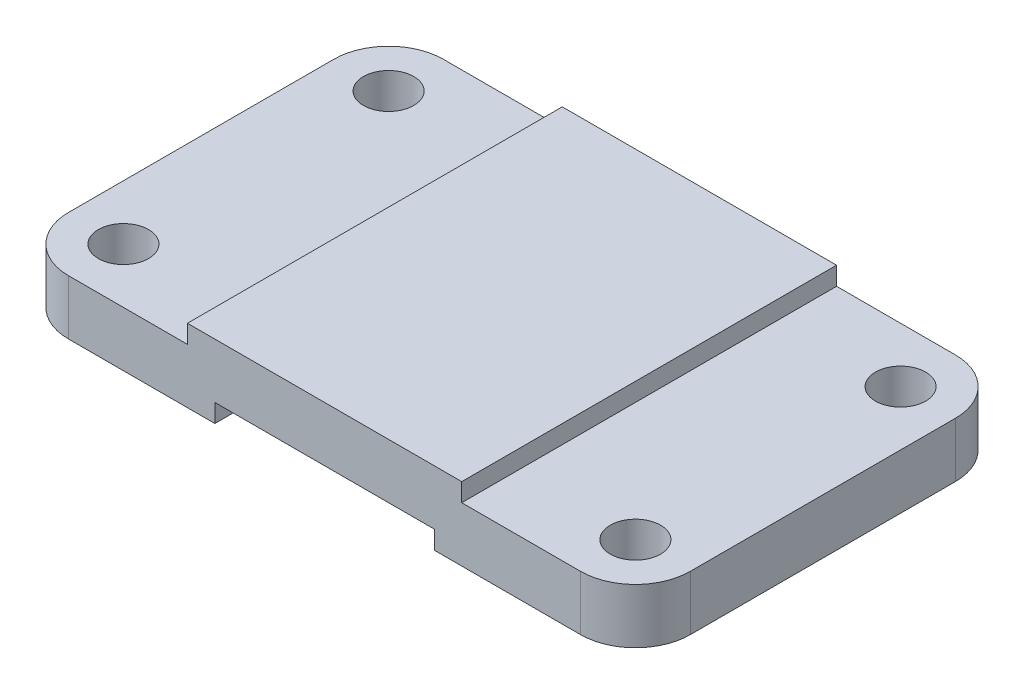
SolidWorks part; units mm, degrees
ref_plane "Plan de face" through (0, 0, 0) normal (0, 0, 1) x (1, 0, 0)
ref_plane "Plan de dessus" through (0, 0, 0) normal (0, 1, 0) x (1, 0, 0)
ref_plane "Plan de droite" through (0, 0, 0) normal (1, 0, 0) x (0, 0, -1)
sketch "Esquisse1" plane through (0, 0, 0) normal (0, 1, 0) x (1, 0, 0)
  line L1 (-68, -41) -> (68, -41)
  line L2 (-68, -41) -> (-68, 41)
  line L3 (-68, 41) -> (68, 41)
  line L4 (68, -41) -> (68, 41)
  line L5 (-68, -41) -> (68, 41) construction
  line L6 (-68, 41) -> (68, -41) construction
  point P0 (0, 0)
  dimension "D1" = 82
  dimension "D2" = 136
extrude "Boss.-Extru.1" add sketch "Esquisse1" along normal blind 16
sketch "Esquisse2" plane through (0, 0, 41) normal (0, 0, 1) x (1, 0, 0)
  line L0 (-68, 0) -> (68, 0) construction
  line L2 (-24, 0) -> (-24, 4)
  line L3 (-24, 4) -> (24, 4)
  line L4 (24, 0) -> (24, 4)
  line L5 (-68, 16) -> (-68, 0) construction
  line L6 (-68, 12) -> (-30, 12)
  line L7 (-68, 12) -> (-68, 16)
  line L9 (-30, 12) -> (-30, 16)
  line L10 (-68, 16) -> (68, 16) construction
  line L11 (68, 16) -> (68, 0) construction
  line L12 (68, 12) -> (30, 12)
  line L13 (68, 12) -> (68, 16)
  line L15 (30, 12) -> (30, 16)
  line L18 (-68, 16) -> (-30, 16)
  line L19 (-24, 0) -> (24, 0)
  line L20 (30, 16) -> (68, 16)
  point P9 (0, 4)
  dimension "D1" = 4
  dimension "D2" = 48
  dimension "D3" = 60
  dimension "D4" = 4
  dimension "D5" = 4
  dimension "D6" = 38
extrude "Enlèv. mat.-Extru.1" cut sketch "Esquisse2" against normal through all
sketch "Esquisse3" plane through (0, 12, 0) normal (0, 1, 0) x (1, 0, 0)
  line L1 (-56, -29) -> (56, -29) construction
  line L2 (-56, -29) -> (-56, 29) construction
  line L3 (-56, 29) -> (56, 29) construction
  line L4 (56, -29) -> (56, 29) construction
  line L5 (-56, -29) -> (56, 29) construction
  line L6 (-56, 29) -> (56, -29) construction
  circle A0 centre (-56, 29) radius 5.5
  circle A1 centre (-56, -29) radius 5.5
  circle A2 centre (56, -29) radius 5.5
  circle A3 centre (56, 29) radius 5.5
  point P0 (0, 0)
  dimension "D3" = 11
  dimension "D4" = 11
  dimension "D5" = 11
  dimension "D6" = 11
  dimension "D1" = 112
  dimension "D2" = 58
extrude "Enlèv. mat.-Extru.3" cut sketch "Esquisse3" against normal through all
fillet "Congé3" radius 12 4 edges at (68, 6, 41) (68, 6, -41) (-68, 6, 41) (-68, 6, -41)
